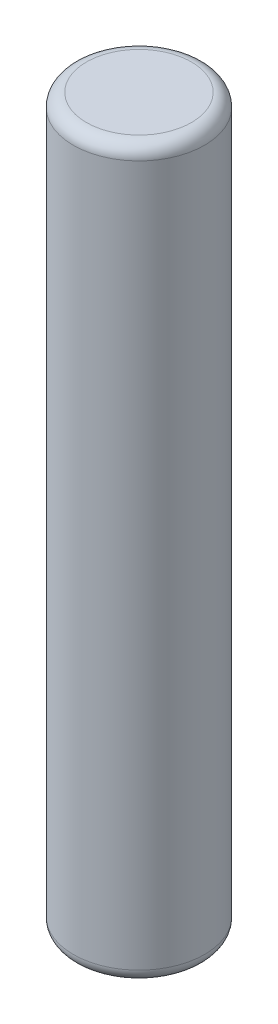
SolidWorks part; units mm, degrees
ref_plane "Front Plane" through (0, 0, 0) normal (0, 0, 1) x (1, 0, 0)
ref_plane "Top Plane" through (0, 0, 0) normal (0, 1, 0) x (1, 0, 0)
ref_plane "Right Plane" through (0, 0, 0) normal (1, 0, 0) x (0, 0, -1)
sketch "Sketch1" plane through (0, 0, 0) normal (0, 1, 0) x (1, 0, 0)
  circle A0 centre (0, 0) radius 2.5
  dimension "D1" = 5
extrude "Boss-Extrude1" add sketch "Sketch1" along normal blind 27.7
fillet "Fillet1" radius 0.5 2 edges at (0, 0, 2.5) (0, 27.7, 2.5)
